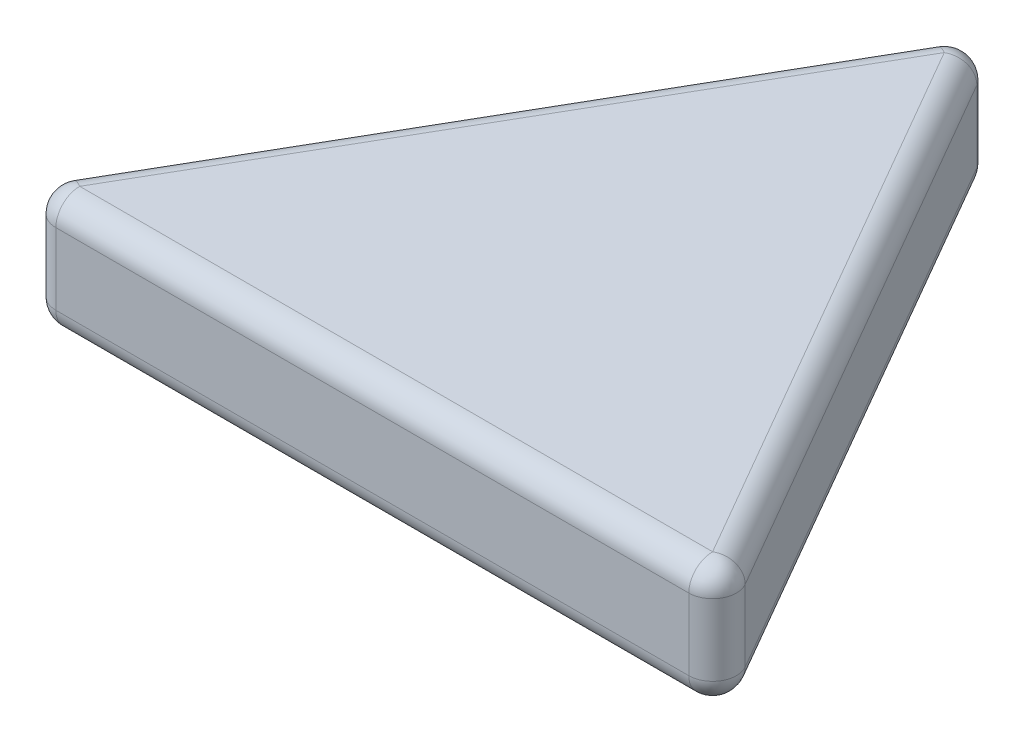
SolidWorks part; units mm, degrees
ref_plane "Front Plane" through (0, 0, 0) normal (0, 0, 1) x (1, 0, 0)
ref_plane "Top Plane" through (0, 0, 0) normal (0, 1, 0) x (1, 0, 0)
ref_plane "Right Plane" through (0, 0, 0) normal (1, 0, 0) x (0, 0, -1)
sketch "Sketch1" plane through (0, 0, 0) normal (0, 1, 0) x (1, 0, 0)
  line L0 (0, 0) -> (15, 25.9808)
  line L1 (15, 25.9808) -> (30, 0)
  line L2 (30, 0) -> (0, 0)
  point P2 (0, 0)
  dimension "D1" = 30
extrude "Boss-Extrude1" add sketch "Sketch1" along normal blind 5
fillet "Fillet1" radius 1 9 edges at (15, 2.5, -25.9808) (7.5, 5, -12.9904) (0, 2.5, 0) (7.5, 0, -12.9904) (22.5, 0, -12.9904) (15, 0, 0) (30, 2.5, 0) (22.5, 5, -12.9904) (15, 5, 0)
